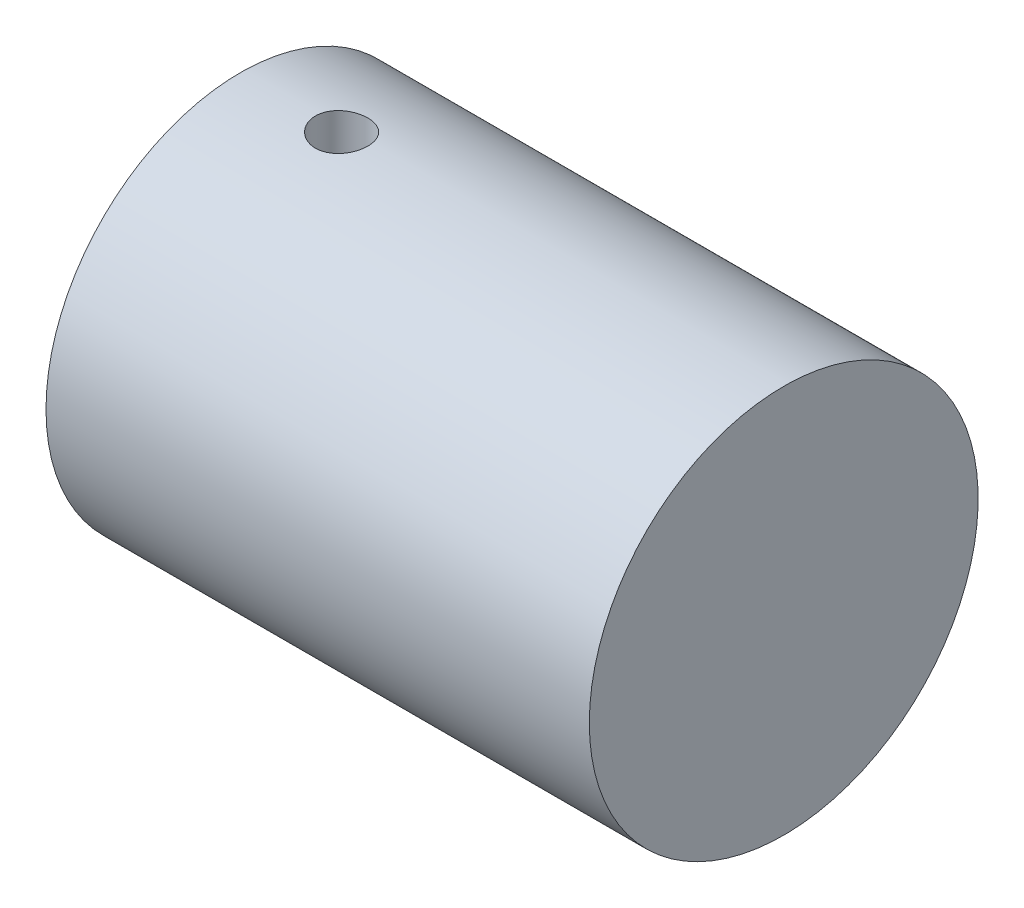
SolidWorks part; units mm, degrees
ref_plane "Plan de face" through (0, 0, 0) normal (0, 0, 1) x (1, 0, 0)
ref_plane "Plan de dessus" through (0, 0, 0) normal (0, 1, 0) x (1, 0, 0)
ref_plane "Plan de droite" through (0, 0, 0) normal (1, 0, 0) x (0, 0, -1)
sketch "Esquisse1" plane through (0, 0, 0) normal (0, 0, 1) x (1, 0, 0)
  line L0 (-22.8879, 0) -> (28.1121, 0)
  line L1 (28.1121, 0) -> (28.1121, 18.25)
  line L2 (28.1121, 18.25) -> (-22.8879, 18.25)
  line L3 (-22.8879, 18.25) -> (-22.8879, 0)
  dimension "D1" = 51
  dimension "D2" = 18.25
revolve "Révolution1" add sketch "Esquisse1" angle 360 about L0
ref_plane "Plan1" through (0, 18.25, 0) normal (0, 1, 0) x (1, 0, 0)
sketch "Esquisse2" plane through (0, 18.25, 0) normal (0, 1, 0) x (1, 0, 0)
  line L0 (-31.4126, 0) -> (4.6368, 0) construction
  line L1 (-22.8879, 18.25) -> (-22.8879, -18.25) construction
  circle A0 centre (-13.3879, 0) radius 2.459
  dimension "D2" = 4.918
  dimension "D1" = 9.5
extrude "Enlèv. mat.-Extru.1" cut sketch "Esquisse2" against normal through all both and the other way through all
sketch "Esquisse3" plane through (28.1121, 0, 0) normal (1, 0, 0) x (0, 0, -1)
  line L1 (-10.25, 10.25) -> (10.25, 10.25)
  line L2 (-10.25, 10.25) -> (-10.25, -10.25)
  line L3 (-10.25, -10.25) -> (10.25, -10.25)
  line L4 (10.25, 10.25) -> (10.25, -10.25)
  line L5 (-10.25, 10.25) -> (10.25, -10.25) construction
  line L6 (-10.25, -10.25) -> (10.25, 10.25) construction
  point P0 (0, 0)
  dimension "D1" = 20.5
  dimension "D2" = 20.5
